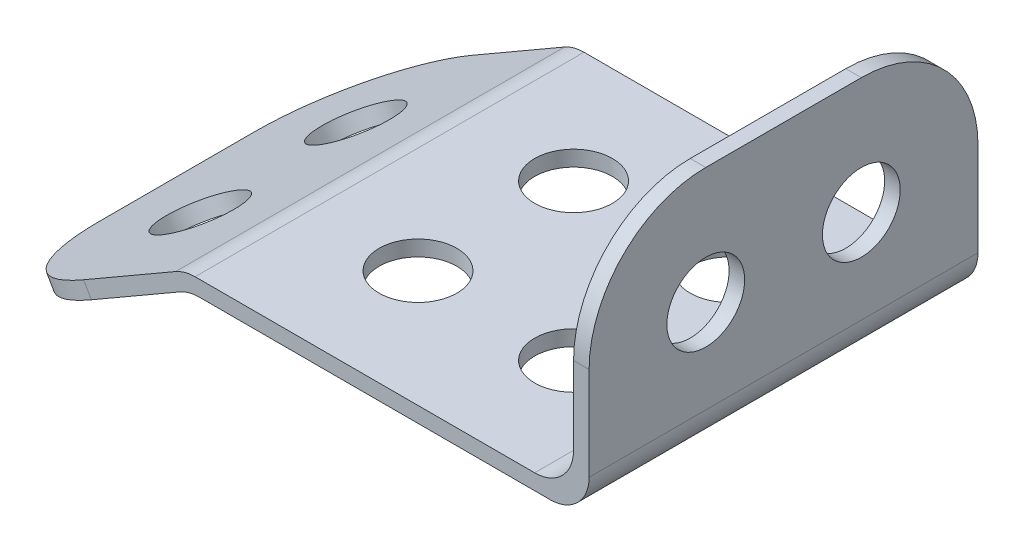
SolidWorks part; units mm, degrees
ref_plane "Front Plane" through (0, 0, 0) normal (0, 0, 1) x (1, 0, 0)
ref_plane "Top Plane" through (0, 0, 0) normal (0, 1, 0) x (1, 0, 0)
ref_plane "Right Plane" through (0, 0, 0) normal (1, 0, 0) x (0, 0, -1)
other "Config1"
sketch "Sketch1" plane through (0, 0, 0) normal (0, 0, 1) x (1, 0, 0)
  line L0 (25, 0) -> (-25, 0)
  line L1 (-25, 0) -> (-50.9808, -15)
  line L2 (25, 0) -> (25, 30)
  point P4 (0, 0)
  point P11 (-25, 0)
  dimension "D1" = 50
  dimension "D2" = 30
  dimension "D3" = 30
  dimension "D4" = 210
extrude "Extrude-Thin1" add sketch "Sketch1" along normal blind 50 thin thin type one direction wall 2
fillet "Fillet1" radius 15 4 edges at (26, 30, 0) (26, 30, 50) (-50.4808, -15.866, 0) (-50.4808, -15.866, 50)
sketch "Sketch2" plane through (0, 0, 0) normal (0, 1, 0) x (1, 0, 0)
  line L0 (-25, 0) -> (25, 0) construction
  line L1 (-25, -50) -> (-25, 0) construction
  circle A0 centre (-10, -15) radius 5
  dimension "D1" = 10
  dimension "D2" = 15
  dimension "D3" = 15
extrude "Cut-Extrude1" cut sketch "Sketch2" against normal up to next
pattern_linear "LPattern1" count 2 spacing 20 along (0, 0, 1) count 2 spacing 20 along (1, 0, 0) of "Cut-Extrude1"
sketch "Sketch3" plane through (-6.25, 10.8253, 0) normal (-0.5, 0.866, 0) x (0.866, 0.5, 0)
  line L0 (-21.6506, -50) -> (-21.6506, 0) construction
  line L1 (-36.6506, 0) -> (-21.6506, 0) construction
  circle A0 centre (-36.6506, -15) radius 5
  circle A1 centre (-36.6506, -35) radius 5
  dimension "D1" = 10
  dimension "D2" = 10
  dimension "D3" = 20
  dimension "D4" = 15
  dimension "D5" = 15
extrude "Cut-Extrude2" cut sketch "Sketch3" against normal up to next
sketch "Sketch4" plane through (25, 0, 0) normal (-1, 0, 0) x (0, 0, 1)
  line L0 (0, 0) -> (0, 15) construction
  line L2 (35, 30) -> (15, 30) construction
  circle A0 centre (15, 15) radius 5
  dimension "D1" = 10
  dimension "D2" = 15
  dimension "D4" = 15
extrude "Cut-Extrude3" cut sketch "Sketch4" against normal through all
pattern_linear "LPattern2" count 2 spacing 20 along (0, 0, 1) of "Cut-Extrude3"
fillet "Fillet2" radius 5 4 edges at (-25, 0, 25) (25, 0, 25) (27, -2, 25) (-24.4641, -2, 25)
